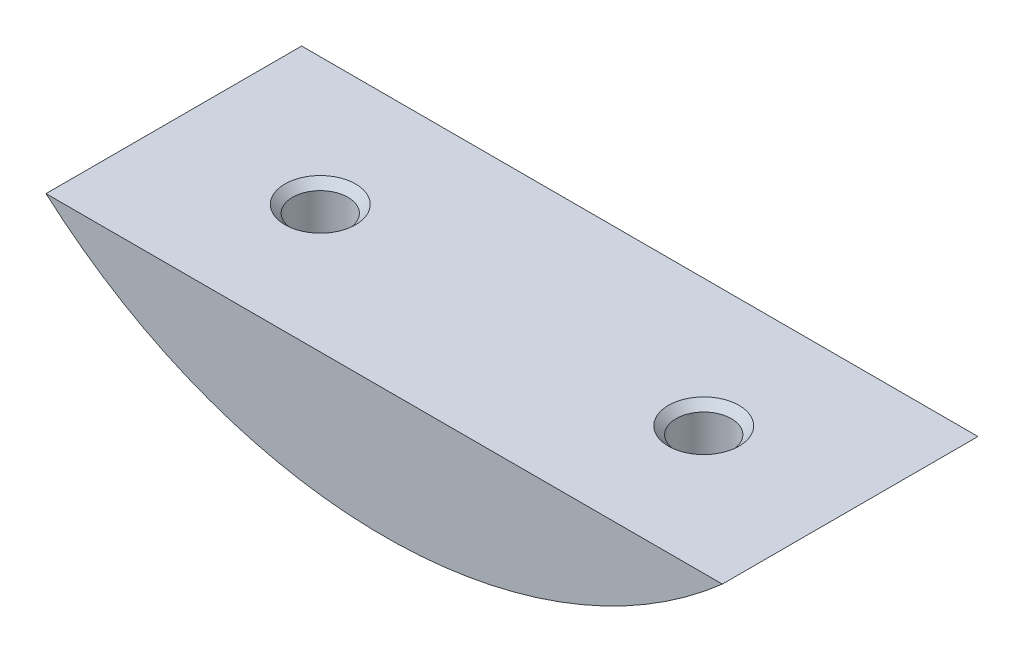
SolidWorks part; units mm, degrees
material "ABS"
ref_plane "Front Plane" through (0, 0, 0) normal (0, 0, 1) x (1, 0, 0)
ref_plane "Top Plane" through (0, 0, 0) normal (0, 1, 0) x (1, 0, 0)
ref_plane "Right Plane" through (0, 0, 0) normal (1, 0, 0) x (0, 0, -1)
sketch "Sketch1" plane through (0, 0, 0) normal (0, 0, 1) x (1, 0, 0)
  line L0 (0, 0) -> (67.2021, 0)
  arc A0 (0, 0) -> (67.2021, 0) centre (33.601, 38.1) ccw
  dimension "D1" = 50.8
  dimension "D2" = 38.1
extrude "Boss-Extrude1" add sketch "Sketch1" along normal blind 25.4
sketch "Sketch2" plane through (0, 0, 0) normal (0, 1, 0) x (1, 0, 0)
  line L0 (0, -12.7) -> (14.551, -12.7) construction
  line L1 (0, -25.4) -> (0, 0) construction
  line L2 (14.551, -12.7) -> (52.651, -12.7) construction
  line L3 (52.651, -12.7) -> (67.2021, -12.7) construction
  line L4 (67.2021, -25.4) -> (67.2021, 0) construction
  circle A0 centre (14.551, -12.7) radius 2
  circle A1 centre (52.651, -12.7) radius 2
  dimension "D2" = 4
  dimension "D1" = 38.1
extrude "Cut-Extrude1" cut sketch "Sketch2" against normal through all both and the other way through all
sketch "Sketch3" plane through (0, 0, 0) normal (0, 1, 0) x (1, 0, 0)
  circle A0 centre (14.551, -12.7) radius 2.75
  circle A1 centre (52.651, -12.7) radius 2.75
  dimension "D1" = 5.5
extrude "Cut-Extrude2" cut sketch "Sketch3" against normal through all
chamfer "Chamfer1" distance 0.762 angle 45 2 edges at (14.551, 0, 15.45) (52.651, 0, 15.45)
